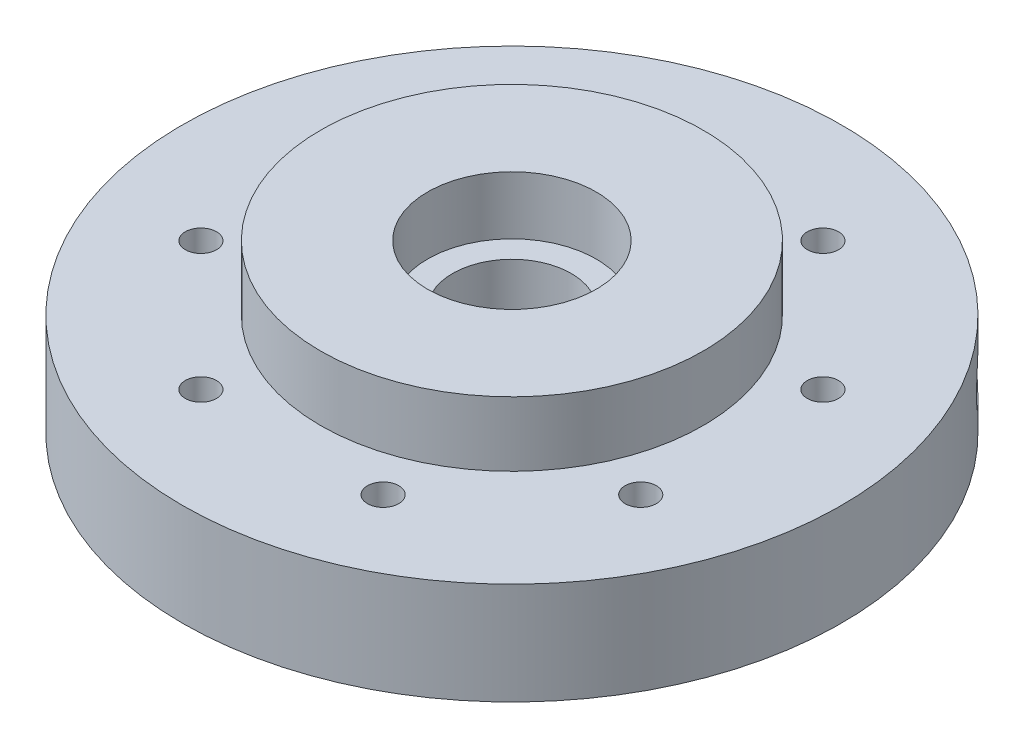
SolidWorks part; units mm, degrees
material "1060 Alloy"
ref_plane "Front" through (0, 0, 0) normal (0, 0, 1) x (1, 0, 0)
ref_plane "Top" through (0, 0, 0) normal (0, 1, 0) x (1, 0, 0)
ref_plane "Right" through (0, 0, 0) normal (1, 0, 0) x (0, 0, -1)
sketch "Sketch1" plane through (0, 0, 0) normal (0, 1, 0) x (1, 0, 0)
  circle A0 centre (0, 0) radius 52.75
  dimension "D1" = 105.5
extrude "base" add sketch "Sketch1" along normal blind 16.3344
sketch "Sketch2" plane through (0, 16.3344, 0) normal (0, 1, 0) x (1, 0, 0)
  circle A0 centre (0, 0) radius 30.6267
  dimension "D1" = 61.2534
sketch "Sketch3" plane through (0, 0, 0) normal (0, -1, 0) x (1, 0, 0)
  circle A0 centre (0, 0) radius 40.75 construction
  circle A1 centre (-40.75, 0) radius 3.5
  circle A2 centre (0, 40.75) radius 3.5
  circle A3 centre (40.75, 0) radius 3.5
  circle A4 centre (0, -40.75) radius 3.5
  point P14 (0, 0)
  dimension "D1" = 81.5
  dimension "D2" = 7
  dimension "D3" = 4
extrude "square bolt holes" cut sketch "Sketch3" against normal blind 14.3344
sketch "Sketch4" plane through (0, 16.3344, 0) normal (0, 1, 0) x (1, 0, 0)
  line L0 (0, 0) -> (0, 38.1) construction
  line L1 (0, 38.1) -> (0, 0) construction
  line L2 (0, 0) -> (14.5802, 35.1998) construction
  circle A0 centre (0, 0) radius 38.1 construction
  circle A1 centre (14.5802, 35.1998) radius 2.5
  dimension "D1" = 76.2
  dimension "D3" = 5
  dimension "D2" = 22.5
extrude "housing bolts" cut sketch "Sketch4" against normal blind 44.33
pattern_circular "CirPattern1" count 8 over 360 about axis through (0, 0, 0) along (0, 1, 0) of "housing bolts"
extrude "impeller cavity riser" add sketch "Sketch2" along normal blind 10.3296
sketch "Sketch5" plane through (0, 26.6639, 0) normal (0, 1, 0) x (1, 0, 0)
  circle A0 centre (0, 0) radius 13.5
  dimension "D1" = 27
extrude "seal bore" cut sketch "Sketch5" against normal blind 9.3
sketch "Sketch6" plane through (0, 17.3639, 0) normal (0, 1, 0) x (1, 0, 0)
  circle A0 centre (0, 0) radius 9.5
  dimension "D1" = 19
extrude "bore" cut sketch "Sketch6" against normal blind 39.3
sketch "pressure tap plane alignment" plane through (0, 0, 0) normal (0, -1, 0) x (1, 0, 0)
  line L0 (0, 0) -> (0, -52.75) construction
  line L1 (0, 0) -> (37.2999, -37.2999) construction
  line L2 (37.2999, -37.2999) -> (74.5998, 0) construction
  line L3 (74.5998, 0) -> (37.2999, 37.2999) construction
  circle A0 centre (0, 0) radius 52.75 construction
  circle A1 centre (0, 0) radius 52.75 construction
  dimension "D1" = 45
ref_plane "pressure tap plane" through (37.2999, 0, -37.2999) normal (0.7071, 0, -0.7071) x (-0.7071, 0, -0.7071)
sketch "Sketch9" plane through (37.2999, 0, -37.2999) normal (0.7071, 0, -0.7071) x (-0.7071, 0, -0.7071)
  line L0 (0, 0) -> (0, 16.3344) construction
  line L1 (52.75, 16.3344) -> (-52.75, 16.3344) construction
  circle A0 centre (0, 8.1672) radius 1.5875
  dimension "D1" = 3.175
extrude "pressure tap" cut sketch "Sketch9" against normal blind 52.75
sketch "Sketch10" plane through (37.2999, 0, -37.2999) normal (0.7071, 0, -0.7071) x (-0.7071, 0, -0.7071)
  circle A0 centre (0, 8.1672) radius 4.1672
  dimension "D1" = 8.3344
extrude "pressure tap bore" cut sketch "Sketch10" against normal blind 12
equation "\"bearing OD\"= 30mm"
equation "\"bearing ID\"= 10mm"
equation "\"bearing depth\"= 9mm"
equation "\"bearing outer race thickness\"= 1mm"
equation "\"bearing inner race thickness\"= 1mm"
equation "\"bearing bore\"= \"bearing depth\" + 1mm"
equation "\"small seal OD\"= 20mm"
equation "\"small seal ID\"= 8mm"
equation "\"small seal depth\"= 8.3mm"
equation "\"small seal bore\"= \"small seal depth\" + 1mm"
equation "\"big seal OD\"= 27mm"
equation "\"big seal ID\"= 15mm"
equation "\"big seal depth\"= 8.3mm"
equation "\"big seal bore\"= \"big seal depth\" + 1mm"
equation "\"z\"= 8 \t\t'number of blades"
equation "\"de\"= 0.426in \t\t'entrance eye diameter"
equation "\"d2\"= 2.097in \t\t'outer diameter of the impeller "
equation "\"d_exit\"= 0.18in \t'volute throat aka D4"
equation "\"theta\"= 15"
equation "\"b2\"= .071in\t\t\t\t\t\t\t'tip height from disc surface at d2"
equation "\"b1\"= \"b2\" + (\"d2\"/2 - \"de\"/2)*sin(\"theta\")\t\t\t'tip height from disc surface at inlet eye"
equation "\"s\"= ( 1/\"z\")*(3.14*\"de\" - (3.14*(\"de\"^2) / (4*(\"b1\"))))\t'thickness of blades, calculated from area"
equation "\"s_opening\"= (3.14*\"de\" - \"z\"*\"s\")/\"z\"\t\t\t\t'ideal gap between blades, calculated from area"
equation "\"area_eye\"=3.14*(\"de\"^2)/4\t\t\t\t\t'eye area"
equation "\"single_channel_area\"=\"s_opening\"*\"b1\"\t\t\t\t'ideal area between two blades"
equation "\"minimum channel width\"= \"s_opening\"\t\t\t\t\t\t\t'minimum s, set this to a bit size for milling or to s_opening for DMLS"
equation "\"inlet area before cut\"= \"minimum channel width\" * (\"z\") * \"b1\"\t\t\t'if minimum channel width>s_opening, this is larger than area_eye"
equation "\"area to cut\"= \"inlet area before cut\" - \"area_eye\"\t\t\t\t\t'amount of extra area\t\t\t\t\t"
equation "\"height to cut\"= \"area to cut\" / ((\"z\")* \"minimum channel width\")+ .0001in\t\t'the 0.0001 in cut is to avoid errors in model"
equation "\"final impeller center height\"= \"impeller base thickness\" + \"b1\" - \"height to cut\"\t'corrected height so that sum of channel areas equals eye area"
equation "\"impeller upper clearance\"= .5mm"
equation "\"impeller horizontal clearance\"= (\"d2\"*1.15 - \"d2\")/2 \t\t\t\t\t'clearance based on D2-D3 ratio for circular volute, ranges 1.15 to 1.2"
equation "\"impeller bottom clearance\"= .5mm"
equation "\"impeller base thickness\"= 2mm"
equation "\"impeller dowel diameter\"= 2mm"
equation "\"impeller bolt head diameter\"= 7.5mm"
equation "\"impeller bolt head depth\"= 4mm"
equation "\"impeller bolt stop depth\"= 3mm"
equation "\"impeller bolt bore\"= 4mm"
equation "\"impeller shaft bore depth\"= 20mm"
equation "\"impeller shaft bore\"= 8mm"
equation "\"impeller boss depth\"= \"impeller shaft bore depth\"+\"impeller bolt stop depth\"+\"impeller bolt head depth\"-\"impeller base thickness\""
equation "\"impeller boss diameter\"= \"big seal ID\""
equation "\"impeller dowel length\"= 2mm*2 + \"impeller shaft bore\""
equation "\"coupler motor shaft hole ID\"= 8mm"
equation "\"coupler OD\"= 17mm"
equation "\"coupler length\"= 25mm"
equation "\"motor OD\"= 64mm"
equation "\"motor shaft diameter\"= 8mm"
equation "\"motor shaft pride\"= 32mm"
equation "\"motor to bearing plate distance\"= \"motor shaft pride\" + 2mm +\"coupler length\"/2"
equation "\"square plate bolt bore\"= 8mm"
equation "\"square plate bolt head diameter\"= 13.5mm"
equation "\"square plate bolt pattern diameter\"= \"motor OD\" + \"square plate bolt head diameter\" + 4mm"
equation "\"motor mount center bore\"= \"coupler OD\"+ 4mm"
equation "\"motor mount post radius\"= ( 3 * \"square plate bolt bore\" ) / 2"
equation "\"motor mount m4 screw hole diameter\"= 4mm"
equation "\"motor mount m4 head diameter\"= 7.25mm"
equation "\"motor mount m4 head depth\"= 4mm"
equation "\"motor mount m4 pattern diamater\"= 30mm"
equation "\"motor mount plate thickness\"= 8mm + \"motor mount m4 head depth\""
equation "\"bearing plate stop ID\"= \"bearing OD\" - 4mm"
equation "\"bearing plate stop depth\"= 3mm"
equation "\"bearing plate thickness\"= \"bearing bore\" + \"bearing plate stop depth\" + \"shaft bearing stop length\""
equation "\"small seal plate lip depth\"= 2mm"
equation "\"small seal plate lip ID\"= \"small seal OD\" - 3mm"
equation "\"small seal plate thickness\"= \"small seal plate lip depth\" + \"small seal bore\""
equation "\"shaft coupler section diameter\"= 8mm"
equation "\"shaft coupler section length\"= \"motor to bearing plate distance\" - \"motor shaft pride\" - 2mm"
equation "\"shaft bearing section diameter\"= \"bearing ID\""
equation "\"shaft bearing section length\"= \"bearing plate stop depth\" + \"bearing depth\""
equation "\"shaft bearing stop diameter\"= \"bearing ID\" + 4mm"
equation "\"shaft bearing stop length\"= 3mm"
equation "\"shaft small seal section diameter\"= \"small seal ID\""
equation "\"shaft small seal section length\"= \"small seal plate thickness\" + 1mm"
equation "\"big seal plate thickness\"= \"big seal plate pressure tap diameter\" + 2*\"big seal plate pressure tap grip\""
equation "\"big seal plate riser\"= \"impeller housing thickness\"/2 - \"b2\"/2 - \"impeller base thickness\" - \t\"impeller bottom clearance\"\t\t\t'this offsets the gap under the housing"
equation "\"big seal plate pressure hole diameter\"= .125in\t'this is 1/8 drill "
equation "\"big seal plate pressure tap diameter\"= .328125in \t'this is 21/64 drill for a 1/8 ANPT tap"
equation "\"big seal plate pressure tap grip\"= 4mm\t\t'this is the area around the tap so it doesn't crack"
equation "\"big seal plate pressure tap depth\"= 12"
equation "\"impeller cavity center height\"= \"impeller bottom clearance\" + \"impeller upper clearance\" + \"final impeller center height\""
equation "\"impeller cavity diameter\"= 2 * \"impeller horizontal clearance\" + \"d2\" \t\t\t\t\t\t\t\t\t'called D3 analytically"
equation "\"impeller cavity outer height\"= \"impeller bottom clearance\" + \"impeller upper clearance\" + \"impeller base thickness\" + \"b2\" \t\t'this is height at impeller diameter d2, not at d3"
equation "\"impeller housing thickness\"= \"impeller housing exit threaded diameter\" + 2*\"impeller housing outlet grip\""
equation "\"impeller housing diameter\"= \"square plate bolt pattern diameter\" + 2*\"motor mount post radius\""
equation "\"impeller housing bolt count\"= 8"
equation "\"impeller housing bolt diameter\"= 6mm"
equation "\"impeller housing bolt pattern diameter\"= 3in"
equation "\"impeller housing threaded inlet diameter\"= 0.6875in \t\t'this is the 11/16 drill size for 1/2 npt fitting"
equation "\"impeller housing threaded inlet depth\"= 15mm"
equation "\"impeller housing exit threaded diameter\"= 0.6875in \t\t'this is the 11/16 drill size for 1/2 npt fitting"
equation "\"impeller housing exit threaded depth\"= 18mm"
equation "\"impeller housing diffuser conical angle\"=10"
equation "\"impeller housing diffuser tangent angle\"=5"
equation "\"impeller housing outlet grip\"= 5mm"
equation "\"D1@Sketch1\"=\"impeller housing diameter\""
equation "\"big seal plate lip ID\"= \"big seal OD\" - 3mm"
equation "\"D1@base\" = \"big seal plate thickness\""
equation "\"D1@Sketch2\"=\"impeller cavity diameter\""
equation "\"D1@Sketch3\"=\"square plate bolt pattern diameter\""
equation "\"D2@Sketch3\"=\"square plate bolt bore\"-1mm"
equation "\"D1@square bolt holes\"=\"big seal plate thickness\" - 2mm"
equation "\"D1@Sketch4\"=\"impeller housing bolt pattern diameter\""
equation "\"D2@Sketch4\"=360/\"impeller housing bolt count\"/2"
equation "\"D3@Sketch4\"=\"impeller housing bolt diameter\"-1mm"
equation "\"D1@CirPattern1\"=\"impeller housing bolt count\""
equation "\"D1@impeller cavity riser\" = \"big seal plate riser\""
equation "\"D1@Sketch5\"=\"big seal OD\""
equation "\"D1@seal bore\" = \"big seal bore\""
equation "\"D1@Sketch6\"=\"big seal ID\"+4mm"
equation "\"D1@Sketch9\"=\"big seal plate pressure hole diameter\""
equation "\"D1@pressure tap\" = \"impeller housing diameter\" / 2"
equation "\"D1@Sketch10\"=\"big seal plate pressure tap diameter\""
equation "\"D1@pressure tap bore\"=\"big seal plate pressure tap depth\""
